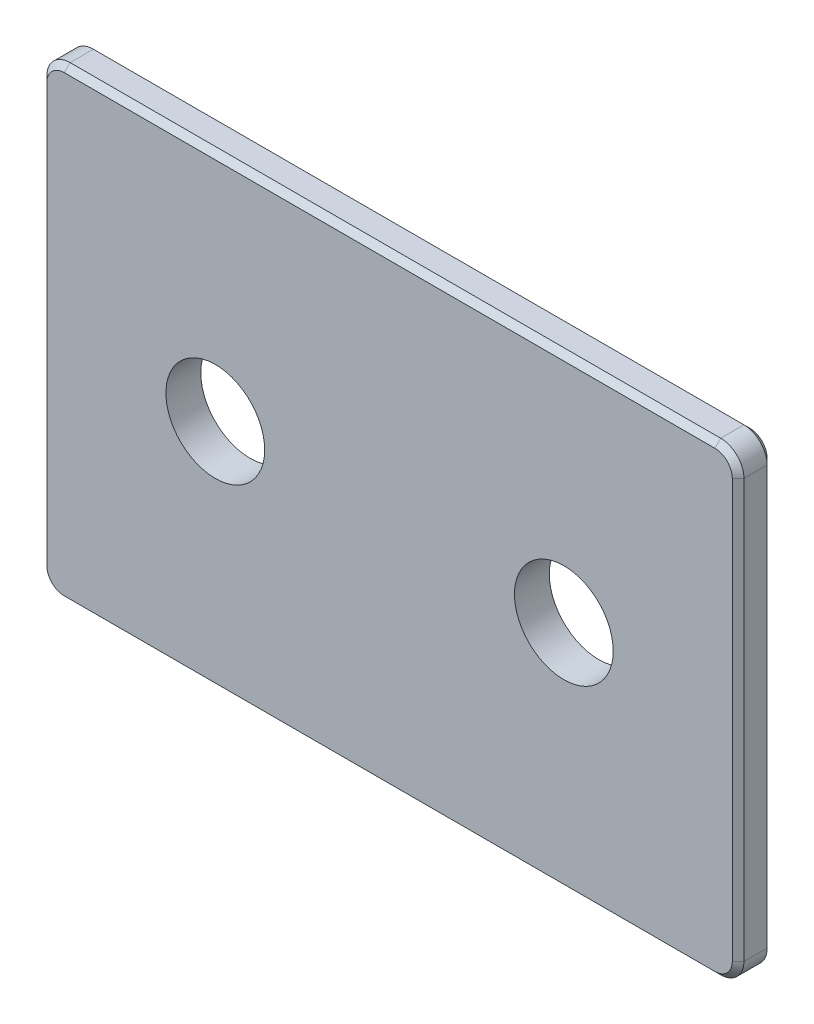
SolidWorks part; units mm, degrees
material "1.0553 (S355J0)"
ref_plane "Płaszczyzna przednia" through (0, 0, 0) normal (0, 0, 1) x (1, 0, 0)
ref_plane "Płaszczyzna górna" through (0, 0, 0) normal (0, 1, 0) x (1, 0, 0)
ref_plane "Płaszczyzna prawa" through (0, 0, 0) normal (1, 0, 0) x (0, 0, -1)
sketch "Szkic1" plane through (0, 0, 0) normal (0, 0, 1) x (1, 0, 0)
  line L1 (0, 0) -> (60, 0)
  line L2 (0, 0) -> (0, 40)
  line L3 (0, 40) -> (60, 40)
  line L4 (60, 0) -> (60, 40)
  dimension "D1" = 40
  dimension "D2" = 60
extrude "Dodanie-wyciągnięcie1" add sketch "Szkic1" along normal blind 3
hole_wizard "Otwór gwintowany M101" positions "Szkic2" profile "Szkic3" tap size "M10" standard "ISO"
sketch "Szkic2" plane through (0, 0, 3) normal (0, 0, 1) x (1, 0, 0)
  line L1 (60, 0) -> (60, 40) construction
  line L2 (60, 40) -> (0, 40) construction
  line L4 (0, 40) -> (0, 0) construction
  point P0 (15, 20)
  point P2 (45, 20)
  dimension "D1" = 15
  dimension "D2" = 15
  dimension "D3" = 20
sketch "Szkic3" plane through (15, 20, 3) normal (1, 0, 0) x (0, -1, 0)
  line L0 (0, 0) -> (0, 30.0537)
  line L1 (0, 30.0537) -> (4.25, 27.5)
  line L2 (4.25, 27.5) -> (4.25, 0)
  line L5 (4.25, 0) -> (0, 0)
  line L10 (0, 30.0537) -> (-4.25, 27.5) construction
  line L11 (0, -6.35) -> (0, 107.95) construction
  dimension "Średnica wiertła gwintu" = 8.5
  dimension "Głębokość otworu gwintowanego" = 27.5
  dimension "Kąt wiertła" = 118
cosmetic thread "Gwint otworu3" parameters "D1"=20, "D2"=10
cosmetic thread "Gwint otworu4" parameters "D1"=20, "D2"=10
fillet "Zaokrąglenie1" radius 2 4 edges at (60, 0, 1.5) (0, 0, 1.5) (0, 40, 1.5) (60, 40, 1.5)
chamfer "Sfazowanie1" distance 0.5 angle 45 16 edges at (59.4142, 0.5858, 0) (60, 20, 0) (59.4142, 39.4142, 0) (30, 40, 0) (0.5858, 39.4142, 0) (0, 20, 0) (0.5858, 0.5858, 0) (30, 0, 0) (59.4142, 0.5858, 3) (60, 20, 3) (59.4142, 39.4142, 3) (30, 40, 3) (0.5858, 39.4142, 3) (0, 20, 3) (0.5858, 0.5858, 3) (30, 0, 3)
